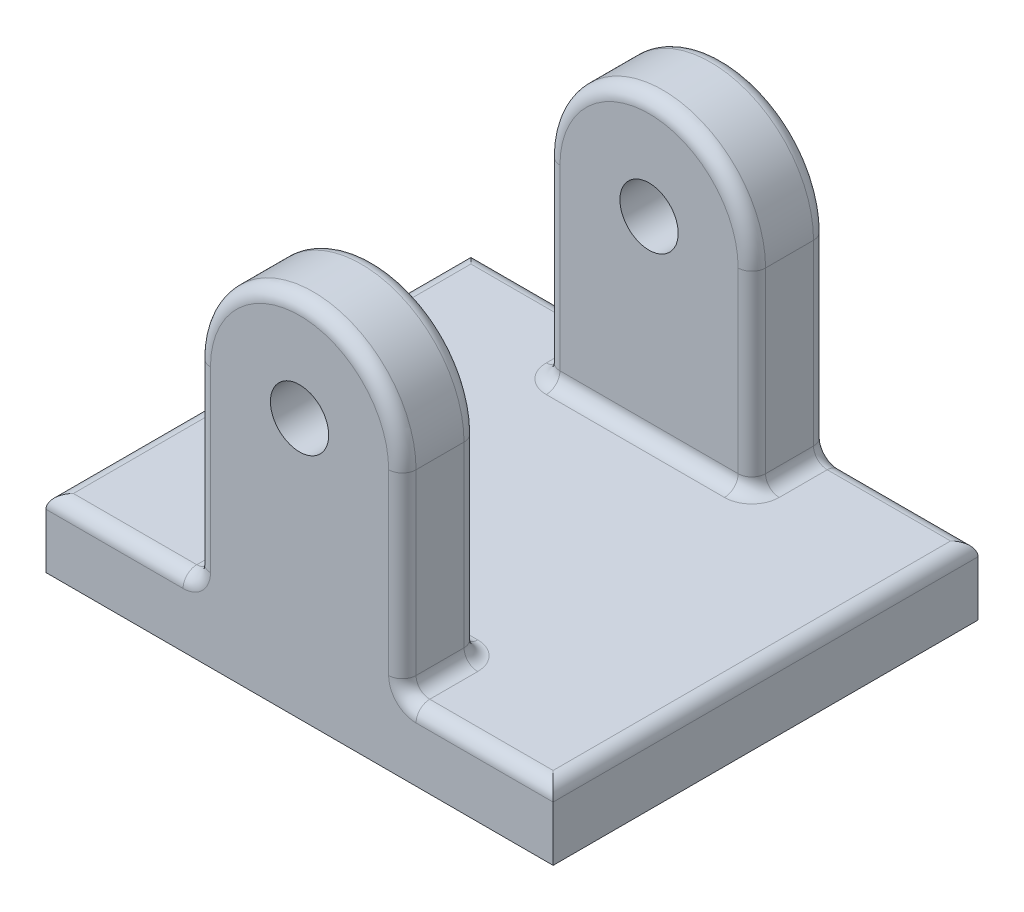
SolidWorks part; units mm, degrees
ref_plane "Front Plane" through (0, 0, 0) normal (0, 0, 1) x (1, 0, 0)
ref_plane "Top Plane" through (0, 0, 0) normal (0, 1, 0) x (1, 0, 0)
ref_plane "Right Plane" through (0, 0, 0) normal (1, 0, 0) x (0, 0, -1)
sketch "Sketch2" plane through (0, 0, 0) normal (0, 1, 0) x (1, 0, 0)
  line L1 (0, 0) -> (74, 0)
  line L2 (0, 0) -> (0, 62)
  line L3 (0, 62) -> (74, 62)
  line L4 (74, 0) -> (74, 62)
  dimension "D1" = 62
  dimension "D2" = 74
extrude "Boss-Extrude1" add sketch "Sketch2" along normal blind 10
sketch "Sketch3" plane through (0, 0, 0) normal (0, 0, 1) x (1, 0, 0)
  line L0 (22, 10) -> (22, 38)
  line L1 (0, 10) -> (74, 10) construction
  line L2 (52, 38) -> (52, 10)
  line L3 (52, 10) -> (22, 10)
  line L4 (0, 0) -> (74, 0) construction
  arc A0 (22, 38) -> (52, 38) centre (37, 38) cw
  point P6 (37, 0)
  dimension "D1" = 38
  dimension "D2" = 15
extrude "Boss-Extrude2" add sketch "Sketch3" against normal blind 11
ref_plane "Plane1" through (0, 0, -31) normal (0, 0, 1) x (1, 0, 0)
mirror "Mirror1" about plane through (0, 0, -31) normal (0, 0, 1) of "Boss-Extrude2", "Boss-Extrude1"
sketch "Sketch5" plane through (0, 0, -62) normal (0, 0, -1) x (-1, 0, 0)
  line L8 (-74, 0) -> (0, 0)
  line L9 (0, 0) -> (0, 10)
  line L10 (0, 10) -> (-22, 10)
  line L11 (-22, 10) -> (-22, 38)
  line L12 (-52, 38) -> (-52, 10)
  line L13 (-52, 10) -> (-74, 10)
  line L14 (-74, 10) -> (-74, 0)
  line L15 (-74, 0) -> (0, 0)
  line L16 (0, 0) -> (0, 10)
  line L17 (0, 10) -> (-22, 10)
  line L18 (-22, 10) -> (-22, 38)
  line L19 (-52, 38) -> (-52, 10)
  line L20 (-52, 10) -> (-74, 10)
  line L21 (-74, 10) -> (-74, 0)
  circle A0 centre (-37, 38) radius 4.25
  arc A2 (-22, 38) -> (-52, 38) centre (-37, 38) ccw
  arc A3 (-22, 38) -> (-52, 38) centre (-37, 38) ccw
  dimension "D1" = 8.5
  dimension "D2" = 0
extrude "Cut-Extrude2" cut sketch "Sketch5" against normal blind 75 contours A0
fillet "Fillet1" radius 2 24 edges at (52, 24, -11) (37, 53, -11) (52, 24, 0) (37, 53, 0) (37, 53, -51) (37, 53, -62) (22, 24, -11) (22, 24, 0) (22, 24, -51) (22, 24, -62) (63, 10, -62) (74, 10, -31) (63, 10, 0) (52, 10, -5.5) (37, 10, -11) (22, 10, -5.5) (11, 10, 0) (0, 10, -31) (11, 10, -62) (22, 10, -56.5) (37, 10, -51) (52, 10, -56.5) (52, 24, -51) (52, 24, -62)
